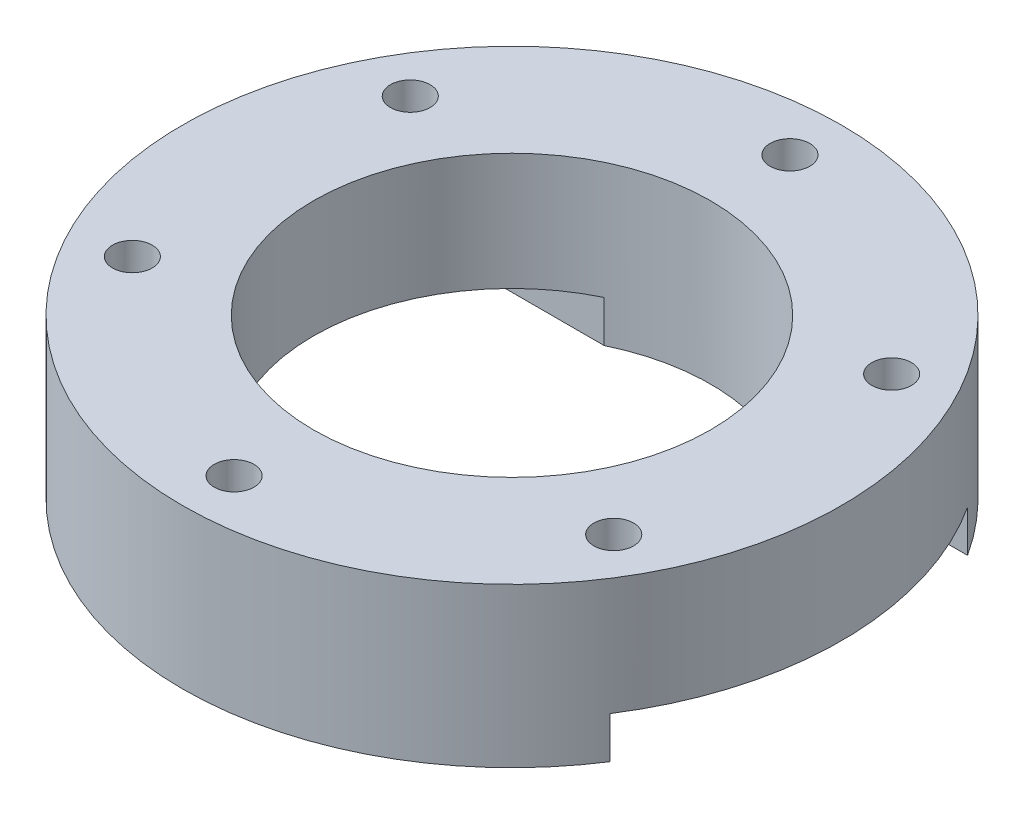
SolidWorks part; units mm, degrees
ref_plane "Ebene vorne" through (0, 0, 0) normal (0, 0, 1) x (1, 0, 0)
ref_plane "Ebene oben" through (0, 0, 0) normal (0, 1, 0) x (1, 0, 0)
ref_plane "Ebene rechts" through (0, 0, 0) normal (1, 0, 0) x (0, 0, -1)
sketch "Sketch1" plane through (0, 0, 0) normal (0, 1, 0) x (1, 0, 0)
  circle A0 centre (0, 0) radius 41.5
  dimension "D1" = 83
extrude "Main Plate" add sketch "Sketch1" along normal blind 20
sketch "Sketch3" plane through (0, 20, 0) normal (0, 1, 0) x (1, 0, 0)
  line L0 (0, 0) -> (0, 41.5) construction
  circle A0 centre (0, 0) radius 41.5 construction
  circle A1 centre (0, 35) radius 2.5
  circle A2 centre (0, 0) radius 25
  circle A3 centre (30.3109, 17.5) radius 2.5
  circle A4 centre (30.3109, -17.5) radius 2.5
  circle A5 centre (0, -35) radius 2.5
  circle A6 centre (-30.3109, -17.5) radius 2.5
  circle A7 centre (-30.3109, 17.5) radius 2.5
  point P22 (0, 0)
  dimension "D3" = 5
  dimension "D4" = 50
  dimension "D1" = 35
  dimension "D2" = 6
extrude "Momo - Sparko" cut sketch "Sketch3" against normal through all
sketch "Sketch4" plane through (0, 0, 0) normal (0, -1, 0) x (1, 0, 0)
  line L1 (45, -22.5) -> (-45, -22.5)
  line L2 (45, -22.5) -> (45, 22.5)
  line L3 (45, 22.5) -> (-45, 22.5)
  line L4 (-45, -22.5) -> (-45, 22.5)
  line L5 (45, -22.5) -> (-45, 22.5) construction
  line L6 (45, 22.5) -> (-45, -22.5) construction
  point P0 (0, 0)
  dimension "D1" = 45
  dimension "D2" = 90
extrude "Cut-Extrude1" cut sketch "Sketch4" against normal blind 5.25
